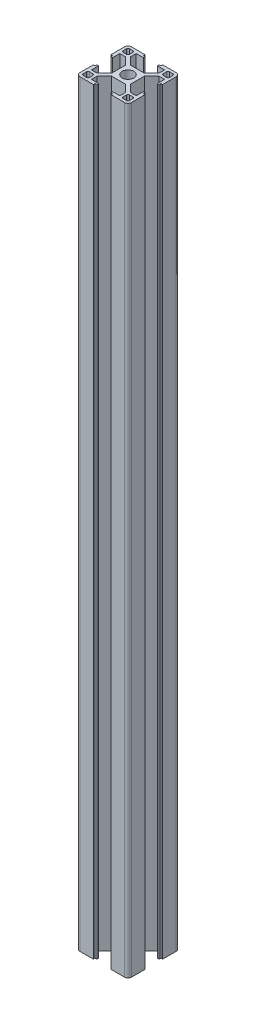
SolidWorks part; units mm, degrees
ref_plane "Front Plane" through (0, 0, 0) normal (0, 0, 1) x (1, 0, 0)
ref_plane "Top Plane" through (0, 0, 0) normal (0, 1, 0) x (1, 0, 0)
ref_plane "Right Plane" through (0, 0, 0) normal (1, 0, 0) x (0, 0, -1)
ref_plane "Plane1" through (0, 0, 0) normal (0, -1, 0) x (1, 0, 0)
sketch "Sketch1" plane through (0, 0, 0) normal (0, -1, 0) x (1, 0, 0)
  line L0 (13.5, -10.75) -> (13.5, -12.5)
  line L1 (12.5, -13.5) -> (10.75, -13.5)
  line L2 (9.75, -12.5) -> (9.75, -10.75)
  line L3 (10.75, -9.75) -> (12.5, -9.75)
  line L4 (-10.75, 9.75) -> (-12.5, 9.75)
  line L5 (-13.5, 10.75) -> (-13.5, 12.5)
  line L6 (-12.5, 13.5) -> (-10.75, 13.5)
  line L7 (-9.75, 12.5) -> (-9.75, 10.75)
  line L8 (12.5, 9.75) -> (10.75, 9.75)
  line L9 (9.75, 10.75) -> (9.75, 12.5)
  line L10 (10.75, 13.5) -> (12.5, 13.5)
  line L11 (13.5, 12.5) -> (13.5, 10.75)
  line L12 (-10.75, -13.5) -> (-12.5, -13.5)
  line L13 (-13.5, -12.5) -> (-13.5, -10.75)
  line L14 (-12.5, -9.75) -> (-10.75, -9.75)
  line L15 (-9.75, -10.75) -> (-9.75, -12.5)
  line L16 (-8.25, 13) -> (-4.1, 13)
  line L17 (-4.1, 13) -> (-4.1, 14)
  line L18 (-4.1, 14) -> (-5.1, 14)
  line L19 (-5.1, 14) -> (-5.1, 15)
  line L20 (-5.1, 15) -> (-13, 15)
  line L21 (-15, 13) -> (-15, 5.1)
  line L22 (-15, 5.1) -> (-14, 5.1)
  line L23 (-14, 5.1) -> (-14, 4.1)
  line L24 (-14, 4.1) -> (-13, 4.1)
  line L25 (-13, 4.1) -> (-13, 8.25)
  line L26 (-13, 8.25) -> (-9.6642, 8.25)
  line L27 (-9.6642, 8.25) -> (-5.5142, 4.1)
  line L28 (-5.5142, 4.1) -> (-5.5142, -4.1)
  line L29 (-5.5142, -4.1) -> (-9.6642, -8.25)
  line L30 (-9.6642, -8.25) -> (-13, -8.25)
  line L31 (-13, -8.25) -> (-13, -4.1)
  line L32 (-13, -4.1) -> (-14, -4.1)
  line L33 (-14, -4.1) -> (-14, -5.1)
  line L34 (-14, -5.1) -> (-15, -5.1)
  line L35 (-15, -5.1) -> (-15, -13)
  line L36 (-13, -15) -> (-5.1, -15)
  line L37 (-5.1, -15) -> (-5.1, -14)
  line L38 (-5.1, -14) -> (-4.1, -14)
  line L39 (-4.1, -14) -> (-4.1, -13)
  line L40 (-4.1, -13) -> (-8.25, -13)
  line L41 (-8.25, -13) -> (-8.25, -9.6642)
  line L42 (-8.25, -9.6642) -> (-4.1, -5.5142)
  line L43 (-4.1, -5.5142) -> (4.1, -5.5142)
  line L44 (4.1, -5.5142) -> (8.25, -9.6642)
  line L45 (8.25, -9.6642) -> (8.25, -13)
  line L46 (8.25, -13) -> (4.1, -13)
  line L47 (4.1, -13) -> (4.1, -14)
  line L48 (4.1, -14) -> (5.1, -14)
  line L49 (5.1, -14) -> (5.1, -15)
  line L50 (5.1, -15) -> (13, -15)
  line L51 (15, -13) -> (15, -5.1)
  line L52 (15, -5.1) -> (14, -5.1)
  line L53 (14, -5.1) -> (14, -4.1)
  line L54 (14, -4.1) -> (13, -4.1)
  line L55 (13, -4.1) -> (13, -8.25)
  line L56 (13, -8.25) -> (9.6642, -8.25)
  line L57 (9.6642, -8.25) -> (5.5142, -4.1)
  line L58 (5.5142, -4.1) -> (5.5142, 4.1)
  line L59 (5.5142, 4.1) -> (9.6642, 8.25)
  line L60 (9.6642, 8.25) -> (13, 8.25)
  line L61 (13, 8.25) -> (13, 4.1)
  line L62 (13, 4.1) -> (14, 4.1)
  line L63 (14, 4.1) -> (14, 5.1)
  line L64 (14, 5.1) -> (15, 5.1)
  line L65 (15, 5.1) -> (15, 13)
  line L66 (13, 15) -> (5.1, 15)
  line L67 (5.1, 15) -> (5.1, 14)
  line L68 (5.1, 14) -> (4.1, 14)
  line L69 (4.1, 14) -> (4.1, 13)
  line L70 (4.1, 13) -> (8.25, 13)
  line L71 (8.25, 13) -> (8.25, 9.6642)
  line L72 (8.25, 9.6642) -> (4.1, 5.5142)
  line L73 (4.1, 5.5142) -> (-4.1, 5.5142)
  line L74 (-4.1, 5.5142) -> (-8.25, 9.6642)
  line L75 (-8.25, 9.6642) -> (-8.25, 13)
  arc A0 (13.5, -12.5) -> (12.5, -13.5) centre (12.5, -12.5) cw
  arc A1 (10.75, -13.5) -> (9.75, -12.5) centre (10.75, -12.5) cw
  arc A2 (9.75, -10.75) -> (10.75, -9.75) centre (10.75, -10.75) cw
  arc A3 (12.5, -9.75) -> (13.5, -10.75) centre (12.5, -10.75) cw
  arc A4 (-9.75, 10.75) -> (-10.75, 9.75) centre (-10.75, 10.75) cw
  arc A5 (-12.5, 9.75) -> (-13.5, 10.75) centre (-12.5, 10.75) cw
  arc A6 (-13.5, 12.5) -> (-12.5, 13.5) centre (-12.5, 12.5) cw
  arc A7 (-10.75, 13.5) -> (-9.75, 12.5) centre (-10.75, 12.5) cw
  circle A8 centre (0, 0) radius 3.4
  arc A9 (10.75, 9.75) -> (9.75, 10.75) centre (10.75, 10.75) cw
  arc A10 (9.75, 12.5) -> (10.75, 13.5) centre (10.75, 12.5) cw
  arc A11 (12.5, 13.5) -> (13.5, 12.5) centre (12.5, 12.5) cw
  arc A12 (13.5, 10.75) -> (12.5, 9.75) centre (12.5, 10.75) cw
  arc A13 (-12.5, -13.5) -> (-13.5, -12.5) centre (-12.5, -12.5) cw
  arc A14 (-13.5, -10.75) -> (-12.5, -9.75) centre (-12.5, -10.75) cw
  arc A15 (-10.75, -9.75) -> (-9.75, -10.75) centre (-10.75, -10.75) cw
  arc A16 (-9.75, -12.5) -> (-10.75, -13.5) centre (-10.75, -12.5) cw
  arc A17 (-13, 15) -> (-15, 13) centre (-13, 13) ccw
  arc A18 (-15, -13) -> (-13, -15) centre (-13, -13) ccw
  arc A19 (13, -15) -> (15, -13) centre (13, -13) ccw
  arc A20 (15, 13) -> (13, 15) centre (13, 13) ccw
extrude "Boss-Extrude1" add sketch "Sketch1" against normal blind 440
